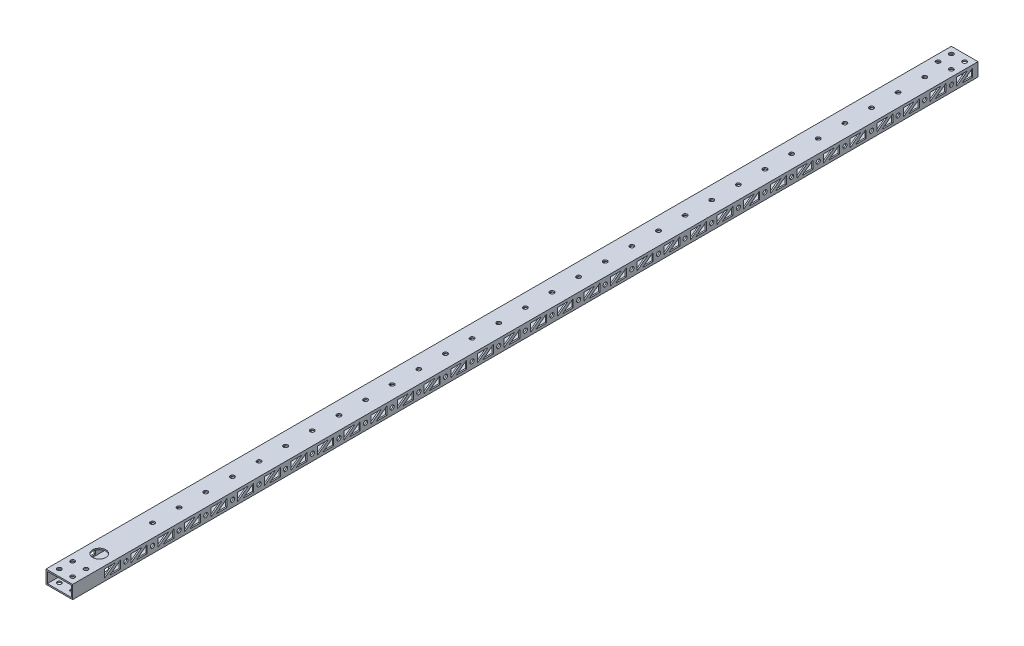
SolidWorks part; units mm, degrees
ref_plane "前视基准面" through (0, 0, 0) normal (0, 0, 1) x (1, 0, 0)
ref_plane "上视基准面" through (0, 0, 0) normal (0, 1, 0) x (1, 0, 0)
ref_plane "右视基准面" through (0, 0, 0) normal (1, 0, 0) x (0, 0, -1)
other "Configuration Table"
sketch "草图1" plane through (0, 0, 0) normal (0, 0, 1) x (1, 0, 0)
  line L1 (0, 0) -> (20, 0)
  line L2 (0, 0) -> (0, -10)
  line L3 (0, -10) -> (20, -10)
  line L4 (20, 0) -> (20, -10)
  dimension "D1" = 20
  dimension "D2" = 10
extrude "拉伸-薄壁1" add sketch "草图1" along normal blind 680 thin
sketch "草图2" plane through (0, -10, 0) normal (0, -1, 0) x (1, 0, 0)
  line L0 (20, 10) -> (0, 10) construction
  line L1 (20, 680) -> (20, 0) construction
  line L2 (0, 680) -> (0, 0) construction
  line L3 (10, 0) -> (10, 10) construction
  line L4 (0, 0) -> (20, 0) construction
  line L5 (10, 10) -> (10, 30) construction
  line L6 (0, 340) -> (20, 340) construction
  line L7 (10, 680) -> (10, 670) construction
  line L8 (20, 670) -> (0, 670) construction
  line L9 (10, 670) -> (10, 650) construction
  circle A0 centre (5, 5) radius 1.575
  circle A1 centre (15, 5) radius 1.575
  circle A2 centre (15, 15) radius 1.575
  circle A3 centre (5, 15) radius 1.575
  circle A4 centre (10, 30) radius 1.575
  circle A5 centre (10, 50) radius 1.575
  circle A6 centre (10, 70) radius 1.575
  circle A7 centre (10, 90) radius 1.575
  circle A8 centre (10, 110) radius 1.575
  circle A9 centre (10, 130) radius 1.575
  circle A10 centre (10, 150) radius 1.575
  circle A11 centre (10, 170) radius 1.575
  circle A12 centre (10, 190) radius 1.575
  circle A13 centre (10, 210) radius 1.575
  circle A14 centre (10, 230) radius 1.575
  circle A15 centre (10, 250) radius 1.575
  circle A16 centre (10, 270) radius 1.575
  circle A17 centre (10, 290) radius 1.575
  circle A18 centre (10, 310) radius 1.575
  circle A19 centre (10, 330) radius 1.575
  circle A20 centre (10, 350) radius 1.575
  circle A21 centre (10, 370) radius 1.575
  circle A22 centre (10, 390) radius 1.575
  circle A23 centre (10, 410) radius 1.575
  circle A24 centre (10, 430) radius 1.575
  circle A25 centre (10, 450) radius 1.575
  circle A26 centre (10, 470) radius 1.575
  circle A27 centre (10, 490) radius 1.575
  circle A28 centre (10, 510) radius 1.575
  circle A29 centre (10, 530) radius 1.575
  circle A30 centre (10, 550) radius 1.575
  circle A31 centre (10, 570) radius 1.575
  circle A32 centre (10, 590) radius 1.575
  circle A33 centre (10, 610) radius 1.575
  circle A37 centre (5, 665) radius 1.575
  circle A38 centre (15, 665) radius 1.575
  circle A39 centre (15, 675) radius 1.575
  circle A40 centre (5, 675) radius 1.575
  circle A41 centre (10, 650) radius 5
  dimension "D1" = 3.15
  dimension "D5" = 3.15
  dimension "D9" = 20
  dimension "D10" = 10
  dimension "D2" = 5
  dimension "D3" = 5
  dimension "D4" = 10
  dimension "D6" = 20
  dimension "D8" = 20
  dimension "D7" = 30
extrude "切除-拉伸1" cut sketch "草图2" against normal through all
sketch "草图4" plane through (20, 0, 0) normal (1, 0, 0) x (0, 0, -1)
  line L0 (0, -5) -> (-680, -5) construction
  line L1 (0, -10) -> (0, 0) construction
  line L2 (-680, -10) -> (-680, 0) construction
  line L3 (-4, -2) -> (-4, -8)
  line L4 (-4, -8) -> (-12, -8)
  line L5 (-12, -8) -> (-4, -2)
  line L6 (-8, -2) -> (-16, -8)
  line L7 (-16, -8) -> (-16, -2)
  line L8 (-16, -2) -> (-8, -2)
  line L9 (-680, -10) -> (0, -10) construction
  line L10 (-680, 0) -> (0, 0) construction
  line L11 (-24, -2) -> (-24, -8)
  line L12 (-24, -8) -> (-32, -8)
  line L13 (-32, -8) -> (-24, -2)
  line L14 (-36, -2) -> (-28, -2)
  line L15 (-28, -2) -> (-36, -8)
  line L16 (-36, -8) -> (-36, -2)
  line L17 (-44, -2) -> (-44, -8)
  line L18 (-44, -8) -> (-52, -8)
  line L19 (-52, -8) -> (-44, -2)
  line L20 (-56, -2) -> (-48, -2)
  line L21 (-48, -2) -> (-56, -8)
  line L22 (-56, -8) -> (-56, -2)
  line L23 (-64, -2) -> (-64, -8)
  line L24 (-64, -8) -> (-72, -8)
  line L25 (-72, -8) -> (-64, -2)
  line L26 (-76, -2) -> (-68, -2)
  line L27 (-68, -2) -> (-76, -8)
  line L28 (-76, -8) -> (-76, -2)
  line L29 (-84, -2) -> (-84, -8)
  line L30 (-84, -8) -> (-92, -8)
  line L31 (-92, -8) -> (-84, -2)
  line L32 (-96, -2) -> (-88, -2)
  line L33 (-88, -2) -> (-96, -8)
  line L34 (-96, -8) -> (-96, -2)
  line L35 (-104, -2) -> (-104, -8)
  line L36 (-104, -8) -> (-112, -8)
  line L37 (-112, -8) -> (-104, -2)
  line L38 (-116, -2) -> (-108, -2)
  line L39 (-108, -2) -> (-116, -8)
  line L40 (-116, -8) -> (-116, -2)
  line L41 (-124, -2) -> (-124, -8)
  line L42 (-124, -8) -> (-132, -8)
  line L43 (-132, -8) -> (-124, -2)
  line L44 (-136, -2) -> (-128, -2)
  line L45 (-128, -2) -> (-136, -8)
  line L46 (-136, -8) -> (-136, -2)
  line L47 (-144, -2) -> (-144, -8)
  line L48 (-144, -8) -> (-152, -8)
  line L49 (-152, -8) -> (-144, -2)
  line L50 (-156, -2) -> (-148, -2)
  line L51 (-148, -2) -> (-156, -8)
  line L52 (-156, -8) -> (-156, -2)
  line L53 (-164, -2) -> (-164, -8)
  line L54 (-164, -8) -> (-172, -8)
  line L55 (-172, -8) -> (-164, -2)
  line L56 (-176, -2) -> (-168, -2)
  line L57 (-168, -2) -> (-176, -8)
  line L58 (-176, -8) -> (-176, -2)
  line L59 (-184, -2) -> (-184, -8)
  line L60 (-184, -8) -> (-192, -8)
  line L61 (-192, -8) -> (-184, -2)
  line L62 (-196, -2) -> (-188, -2)
  line L63 (-188, -2) -> (-196, -8)
  line L64 (-196, -8) -> (-196, -2)
  line L65 (-204, -2) -> (-204, -8)
  line L66 (-204, -8) -> (-212, -8)
  line L67 (-212, -8) -> (-204, -2)
  line L68 (-216, -2) -> (-208, -2)
  line L69 (-208, -2) -> (-216, -8)
  line L70 (-216, -8) -> (-216, -2)
  line L71 (-224, -2) -> (-224, -8)
  line L72 (-224, -8) -> (-232, -8)
  line L73 (-232, -8) -> (-224, -2)
  line L74 (-236, -2) -> (-228, -2)
  line L75 (-228, -2) -> (-236, -8)
  line L76 (-236, -8) -> (-236, -2)
  line L77 (-244, -2) -> (-244, -8)
  line L78 (-244, -8) -> (-252, -8)
  line L79 (-252, -8) -> (-244, -2)
  line L80 (-256, -2) -> (-248, -2)
  line L81 (-248, -2) -> (-256, -8)
  line L82 (-256, -8) -> (-256, -2)
  line L83 (-264, -2) -> (-264, -8)
  line L84 (-264, -8) -> (-272, -8)
  line L85 (-272, -8) -> (-264, -2)
  line L86 (-276, -2) -> (-268, -2)
  line L87 (-268, -2) -> (-276, -8)
  line L88 (-276, -8) -> (-276, -2)
  line L89 (-284, -2) -> (-284, -8)
  line L90 (-284, -8) -> (-292, -8)
  line L91 (-292, -8) -> (-284, -2)
  line L92 (-296, -2) -> (-288, -2)
  line L93 (-288, -2) -> (-296, -8)
  line L94 (-296, -8) -> (-296, -2)
  line L95 (-304, -2) -> (-304, -8)
  line L96 (-304, -8) -> (-312, -8)
  line L97 (-312, -8) -> (-304, -2)
  line L98 (-316, -2) -> (-308, -2)
  line L99 (-308, -2) -> (-316, -8)
  line L100 (-316, -8) -> (-316, -2)
  line L101 (-324, -2) -> (-324, -8)
  line L102 (-324, -8) -> (-332, -8)
  line L103 (-332, -8) -> (-324, -2)
  line L104 (-336, -2) -> (-328, -2)
  line L105 (-328, -2) -> (-336, -8)
  line L106 (-336, -8) -> (-336, -2)
  line L107 (-344, -2) -> (-344, -8)
  line L108 (-344, -8) -> (-352, -8)
  line L109 (-352, -8) -> (-344, -2)
  line L110 (-356, -2) -> (-348, -2)
  line L111 (-348, -2) -> (-356, -8)
  line L112 (-356, -8) -> (-356, -2)
  line L113 (-364, -2) -> (-364, -8)
  line L114 (-364, -8) -> (-372, -8)
  line L115 (-372, -8) -> (-364, -2)
  line L116 (-376, -2) -> (-368, -2)
  line L117 (-368, -2) -> (-376, -8)
  line L118 (-376, -8) -> (-376, -2)
  line L119 (-384, -2) -> (-384, -8)
  line L120 (-384, -8) -> (-392, -8)
  line L121 (-392, -8) -> (-384, -2)
  line L122 (-396, -2) -> (-388, -2)
  line L123 (-388, -2) -> (-396, -8)
  line L124 (-396, -8) -> (-396, -2)
  line L125 (-404, -2) -> (-404, -8)
  line L126 (-404, -8) -> (-412, -8)
  line L127 (-412, -8) -> (-404, -2)
  line L128 (-416, -2) -> (-408, -2)
  line L129 (-408, -2) -> (-416, -8)
  line L130 (-416, -8) -> (-416, -2)
  line L131 (-424, -2) -> (-424, -8)
  line L132 (-424, -8) -> (-432, -8)
  line L133 (-432, -8) -> (-424, -2)
  line L134 (-436, -2) -> (-428, -2)
  line L135 (-428, -2) -> (-436, -8)
  line L136 (-436, -8) -> (-436, -2)
  line L137 (-444, -2) -> (-444, -8)
  line L138 (-444, -8) -> (-452, -8)
  line L139 (-452, -8) -> (-444, -2)
  line L140 (-456, -2) -> (-448, -2)
  line L141 (-448, -2) -> (-456, -8)
  line L142 (-456, -8) -> (-456, -2)
  line L143 (-464, -2) -> (-464, -8)
  line L144 (-464, -8) -> (-472, -8)
  line L145 (-472, -8) -> (-464, -2)
  line L146 (-476, -2) -> (-468, -2)
  line L147 (-468, -2) -> (-476, -8)
  line L148 (-476, -8) -> (-476, -2)
  line L149 (-484, -2) -> (-484, -8)
  line L150 (-484, -8) -> (-492, -8)
  line L151 (-492, -8) -> (-484, -2)
  line L152 (-496, -2) -> (-488, -2)
  line L153 (-488, -2) -> (-496, -8)
  line L154 (-496, -8) -> (-496, -2)
  line L155 (-504, -2) -> (-504, -8)
  line L156 (-504, -8) -> (-512, -8)
  line L157 (-512, -8) -> (-504, -2)
  line L158 (-516, -2) -> (-508, -2)
  line L159 (-508, -2) -> (-516, -8)
  line L160 (-516, -8) -> (-516, -2)
  line L161 (-524, -2) -> (-524, -8)
  line L162 (-524, -8) -> (-532, -8)
  line L163 (-532, -8) -> (-524, -2)
  line L164 (-536, -2) -> (-528, -2)
  line L165 (-528, -2) -> (-536, -8)
  line L166 (-536, -8) -> (-536, -2)
  line L167 (-544, -2) -> (-544, -8)
  line L168 (-544, -8) -> (-552, -8)
  line L169 (-552, -8) -> (-544, -2)
  line L170 (-556, -2) -> (-548, -2)
  line L171 (-548, -2) -> (-556, -8)
  line L172 (-556, -8) -> (-556, -2)
  line L173 (-564, -2) -> (-564, -8)
  line L174 (-564, -8) -> (-572, -8)
  line L175 (-572, -8) -> (-564, -2)
  line L176 (-576, -2) -> (-568, -2)
  line L177 (-568, -2) -> (-576, -8)
  line L178 (-576, -8) -> (-576, -2)
  line L179 (-584, -2) -> (-584, -8)
  line L180 (-584, -8) -> (-592, -8)
  line L181 (-592, -8) -> (-584, -2)
  line L182 (-596, -2) -> (-588, -2)
  line L183 (-588, -2) -> (-596, -8)
  line L184 (-596, -8) -> (-596, -2)
  line L185 (-604, -2) -> (-604, -8)
  line L186 (-604, -8) -> (-612, -8)
  line L187 (-612, -8) -> (-604, -2)
  line L188 (-616, -2) -> (-608, -2)
  line L189 (-608, -2) -> (-616, -8)
  line L190 (-616, -8) -> (-616, -2)
  line L191 (-624, -2) -> (-624, -8)
  line L192 (-624, -8) -> (-632, -8)
  line L193 (-632, -8) -> (-624, -2)
  line L194 (-636, -2) -> (-628, -2)
  line L195 (-628, -2) -> (-636, -8)
  line L196 (-636, -8) -> (-636, -2)
  line L197 (-644, -2) -> (-644, -8)
  line L198 (-644, -8) -> (-652, -8)
  line L199 (-652, -8) -> (-644, -2)
  line L200 (-656, -2) -> (-648, -2)
  line L201 (-648, -2) -> (-656, -8)
  line L202 (-656, -8) -> (-656, -2)
  line L215 (-664, -2) -> (-664, -8) [skipped]
  line L216 (-664, -8) -> (-672, -8) [skipped]
  line L217 (-672, -8) -> (-664, -2) [skipped]
  line L218 (-676, -2) -> (-668, -2) [skipped]
  line L219 (-668, -2) -> (-676, -8) [skipped]
  line L220 (-676, -8) -> (-676, -2) [skipped]
  line L221 (-684, -2) -> (-684, -8) [skipped]
  line L222 (-684, -8) -> (-692, -8) [skipped]
  line L223 (-692, -8) -> (-684, -2) [skipped]
  line L224 (-696, -2) -> (-688, -2) [skipped]
  line L225 (-688, -2) -> (-696, -8) [skipped]
  line L226 (-696, -8) -> (-696, -2) [skipped]
  circle A0 centre (-20, -5) radius 1.575
  circle A1 centre (-40, -5) radius 1.575
  circle A2 centre (-60, -5) radius 1.575
  circle A3 centre (-80, -5) radius 1.575
  circle A4 centre (-100, -5) radius 1.575
  circle A5 centre (-120, -5) radius 1.575
  circle A6 centre (-140, -5) radius 1.575
  circle A7 centre (-160, -5) radius 1.575
  circle A8 centre (-180, -5) radius 1.575
  circle A9 centre (-200, -5) radius 1.575
  circle A10 centre (-220, -5) radius 1.575
  circle A11 centre (-240, -5) radius 1.575
  circle A12 centre (-260, -5) radius 1.575
  circle A13 centre (-280, -5) radius 1.575
  circle A14 centre (-300, -5) radius 1.575
  circle A15 centre (-320, -5) radius 1.575
  circle A16 centre (-340, -5) radius 1.575
  circle A17 centre (-360, -5) radius 1.575
  circle A18 centre (-380, -5) radius 1.575
  circle A19 centre (-400, -5) radius 1.575
  circle A20 centre (-420, -5) radius 1.575
  circle A21 centre (-440, -5) radius 1.575
  circle A22 centre (-460, -5) radius 1.575
  circle A23 centre (-480, -5) radius 1.575
  circle A24 centre (-500, -5) radius 1.575
  circle A25 centre (-520, -5) radius 1.575
  circle A26 centre (-540, -5) radius 1.575
  circle A27 centre (-560, -5) radius 1.575
  circle A28 centre (-580, -5) radius 1.575
  circle A29 centre (-600, -5) radius 1.575
  circle A30 centre (-620, -5) radius 1.575
  circle A31 centre (-640, -5) radius 1.575
  circle A36 centre (-660, -5) radius 1.575 [skipped]
  circle A37 centre (-680, -5) radius 1.575 [skipped]
  dimension "D2" = 3.15
  dimension "D1" = 20
  dimension "D3" = 20
  dimension "D4" = 8
  dimension "D5" = 6
  dimension "D6" = 6
  dimension "D7" = 2
  dimension "D8" = 2
  dimension "D9" = 12
  dimension "D10" = 4
  dimension "D12" = 20
  dimension "D11" = 35
extrude "切除-拉伸2" cut sketch "草图4" against normal through all
